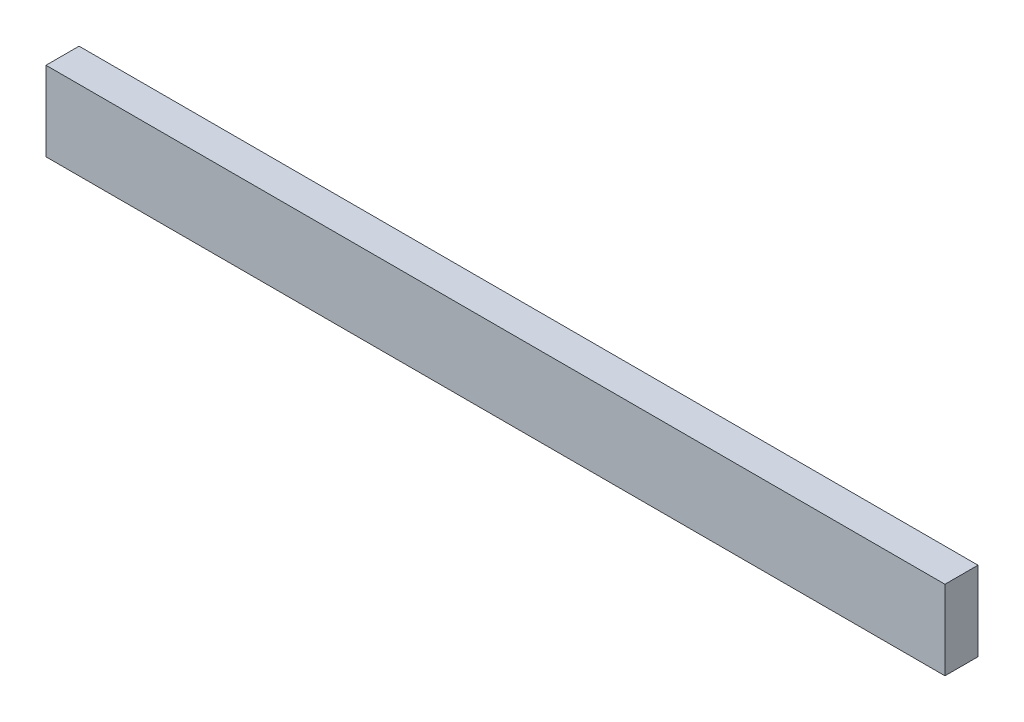
SolidWorks part; units mm, degrees
ref_plane "Plan de face" through (0, 0, 0) normal (0, 0, 1) x (1, 0, 0)
ref_plane "Plan de dessus" through (0, 0, 0) normal (0, 1, 0) x (1, 0, 0)
ref_plane "Plan de droite" through (0, 0, 0) normal (1, 0, 0) x (0, 0, -1)
sketch "Esquisse1" plane through (0, 0, 0) normal (0, 0, 1) x (1, 0, 0)
  line L1 (0, 0) -> (680, 0)
  line L2 (0, 0) -> (0, 60)
  line L3 (0, 60) -> (680, 60)
  line L4 (680, 0) -> (680, 60)
  dimension "D1" = 680
  dimension "D2" = 60
extrude "Boss.-Extru.1" add sketch "Esquisse1" along normal blind 25
